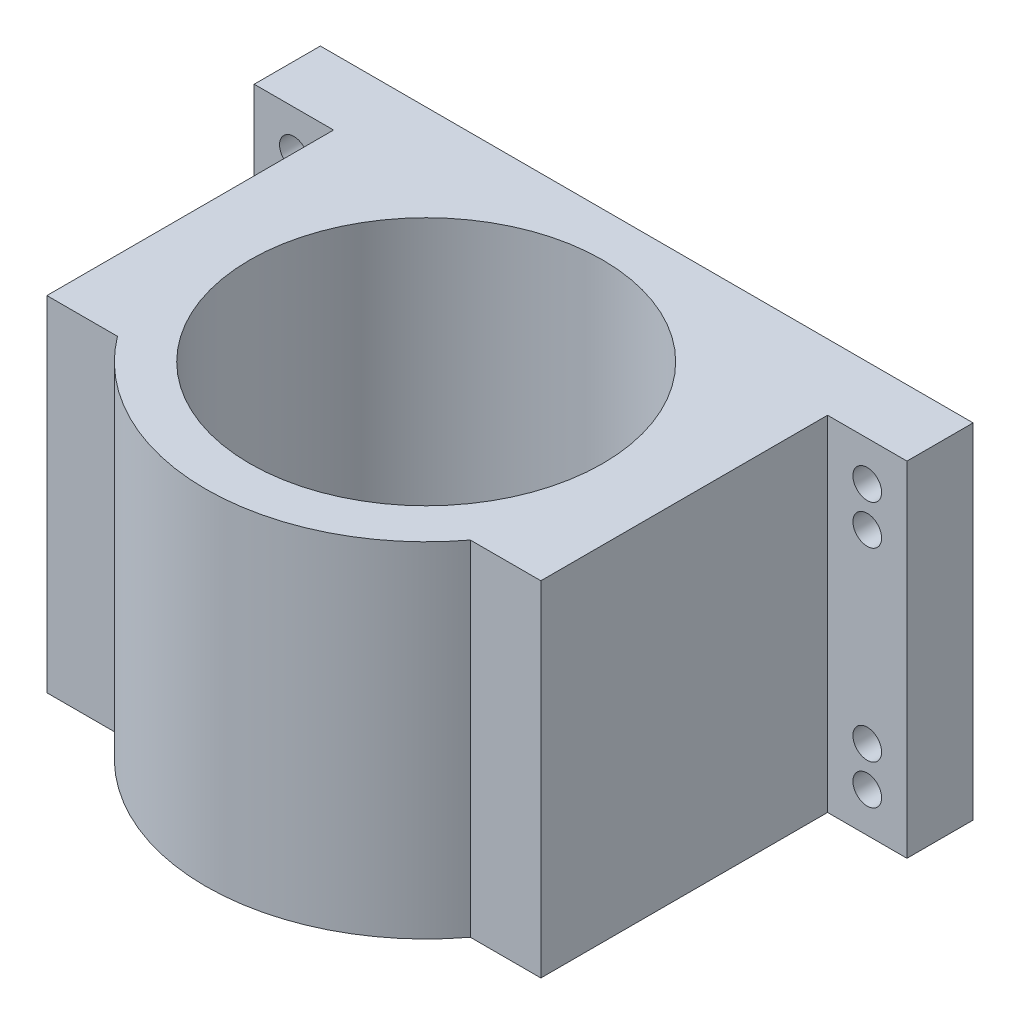
SolidWorks part; units mm, degrees
ref_plane "Front Plane" through (0, 0, 0) normal (0, 0, 1) x (1, 0, 0)
ref_plane "Top Plane" through (0, 0, 0) normal (0, 1, 0) x (1, 0, 0)
ref_plane "Right Plane" through (0, 0, 0) normal (1, 0, 0) x (0, 0, -1)
sketch "Sketch1" plane through (0, 0, 0) normal (0, 1, 0) x (1, 0, 0)
  line L0 (0, 0) -> (0, 56.3493) construction
  line L1 (-74, 50) -> (74, 50)
  line L2 (74, 50) -> (74, 35)
  line L3 (74, 35) -> (56, 35)
  line L4 (56, 35) -> (56, -30)
  line L5 (56, -30) -> (40, -30)
  line L6 (-56, -30) -> (-40, -30)
  line L7 (-56, 35) -> (-56, -30)
  line L8 (-74, 35) -> (-56, 35)
  line L9 (-74, 50) -> (-74, 35)
  circle A0 centre (0, 0) radius 40
  circle A1 centre (0, 0) radius 50
  point P16 (0, 50)
  dimension "D5" = 80
  dimension "D6" = 10
  dimension "D1" = 74
  dimension "D2" = 15
  dimension "D3" = 18
  dimension "D4" = 65
extrude "Boss-Extrude1" add sketch "Sketch1" along normal blind 78
sketch "Sketch2" plane through (0, 0, -35) normal (0, 0, 1) x (1, 0, 0)
  line L0 (65, 78) -> (65, 0) construction
  line L1 (74, 78) -> (56, 78) construction
  line L2 (74, 0) -> (56, 0) construction
  line L3 (74, 39) -> (56, 39) construction
  line L4 (74, 78) -> (74, 0) construction
  line L5 (56, 78) -> (56, 0) construction
  line L6 (69, 60) -> (69, 66)
  line L7 (61, 60) -> (61, 66)
  circle A0 centre (65, 69) radius 5
  circle A1 centre (65, 69) radius 9 construction
  circle A3 centre (65, 60) radius 4
  dimension "D1" = 10
hole_wizard "Ø6.5 (6.5) Diameter Hole1" positions "3DSketch3" profile "Sketch6" hole size "Ø6.5" standard "ANSI Metric" end condition up to next
sketch3d "3DSketch3"
  point P0 (65, 69, -35)
  point P3 (65, 60, -35)
sketch "Sketch6" plane through (65, 69, -35) normal (1, 0, 0) x (0, -1, 0)
  line L0 (0, 0) -> (0, 15)
  line L1 (0, 15) -> (3.25, 15)
  line L2 (3.25, 15) -> (3.25, 0)
  line L5 (3.25, 0) -> (0, 0)
  line L11 (0, -6.35) -> (0, 107.95) construction
  dimension "Thru Hole Dia." = 6.5
  dimension "Thru Hole Depth" = 15
ref_plane "Plane1" through (0, 0, 0) normal (1, 0, 0) x (0, 0, -1)
ref_plane "Plane2" through (0, 39, 0) normal (0, 1, 0) x (1, 0, 0)
mirror "Mirror2" about plane through (0, 39, 0) normal (0, 1, 0) of "Ø6.5 (6.5) Diameter Hole1" second plane through (0, 0, 0) second plane normal (1, 0, 0)
